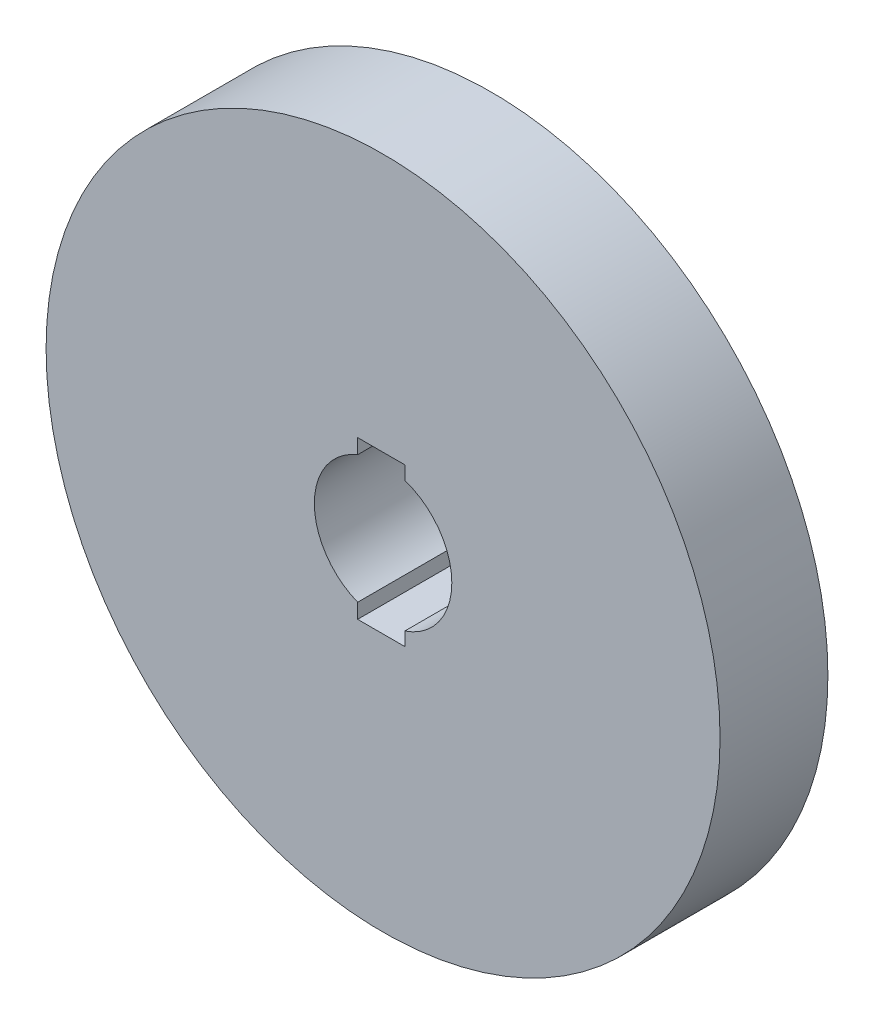
SolidWorks part; units mm, degrees
ref_plane "Front Plane" through (0, 0, 0) normal (1, 0, 0) x (0, 1, 0)
ref_plane "Top Plane" through (0, 0, 0) normal (0, 0, 1) x (0, 1, 0)
ref_plane "Right Plane" through (0, 0, 0) normal (0, 1, 0) x (-1, 0, 0)
sketch "Sketch1" plane through (0, 0, 0) normal (0, 0, 1) x (0, 1, 0)
  line L0 (-1.8946, 4.4646) -> (-1.8946, 5.4646)
  line L1 (-1.8946, -5.9286) -> (1.5357, -5.9286)
  line L2 (-1.8946, -5.9286) -> (-1.8946, -4.9286)
  line L3 (-1.8946, 5.4646) -> (1.5357, 5.4646)
  line L4 (1.5357, -5.9286) -> (1.5357, -4.9286)
  line L5 (1.5357, 4.4646) -> (1.5357, 5.4646)
  circle A0 centre (0, 0) radius 25
  arc A1 (1.5357, -4.9286) -> (1.5357, 4.4646) centre (-0.1794, -0.232) ccw
  arc A2 (-1.8946, 4.4646) -> (-1.8946, -4.9286) centre (-0.1794, -0.232) ccw
  dimension "D1" = 50
  dimension "D2" = 1
extrude "Boss-Extrude1" add sketch "Sketch1" along normal blind 8 contours A0
sketch "Sketch2" plane through (0, 0, 8) normal (0, 0, 1) x (1, 0, 0)
  line L0 (-1.8863, 4.7383) -> (-1.8863, 5.8383)
  line L1 (-1.8863, -5.8383) -> (1.6126, -5.8383)
  line L2 (-1.8863, -5.8383) -> (-1.8863, -4.7383)
  line L3 (-1.8863, 5.8383) -> (1.6126, 5.8383)
  line L4 (1.6126, -5.8383) -> (1.6126, -4.8383)
  line L5 (1.6126, 4.8383) -> (1.6126, 5.8383)
  arc A0 (1.6126, -4.8383) -> (1.6126, 4.8383) centre (0, 0) ccw
  arc A1 (-1.8863, 4.7383) -> (-1.8863, -4.7383) centre (0, 0) ccw
  dimension "D2" = 0
  dimension "D3" = 5.1
  dimension "D1" = 1
  dimension "D4" = 1.1
  dimension "D5" = 1.1
extrude "Cut-Extrude1" cut sketch "Sketch2" against normal through all
